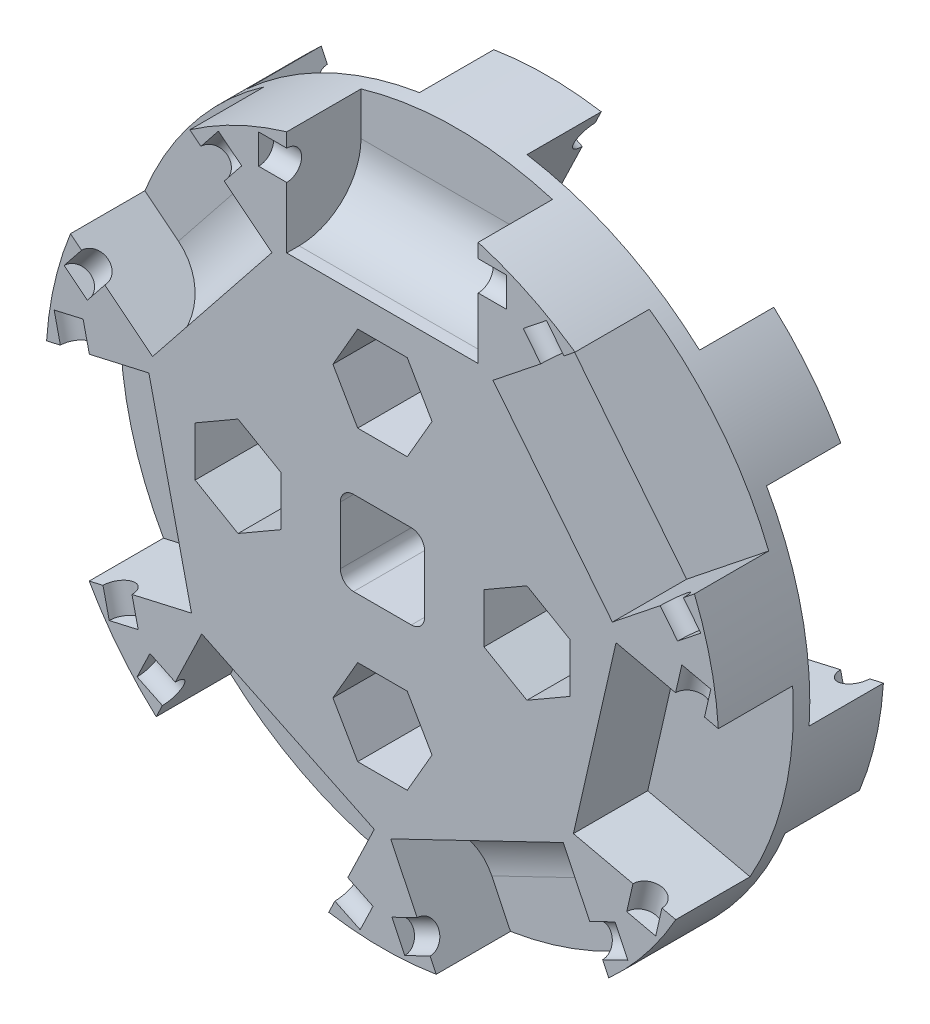
SolidWorks part; units mm, degrees
other "Markup1"
sketch "Sketch8" plane through (32.7336, 32.7336, 0) normal (0.5701, 0.1846, 0.8006) x (0.8043, 0.0736, -0.5897)
ref_plane "Front Plane" through (0, 0, 0) normal (0, 0, 1) x (1, 0, 0)
ref_plane "Top Plane" through (0, 0, 0) normal (0, 1, 0) x (1, 0, 0)
ref_plane "Right Plane" through (0, 0, 0) normal (1, 0, 0) x (0, 0, -1)
sketch "Sketch1" plane through (0, 0, 0) normal (0, 0, 1) x (1, 0, 0)
  circle A0 centre (0, 0) radius 25.8953
  dimension "D1" = 51.7906
extrude "Boss-Extrude2" add sketch "Sketch1" against normal blind 6.35
sketch "Sketch2" plane through (0, 0, 0) normal (0, 0, 1) x (1, 0, 0)
  line L1 (-12.7, 25.8953) -> (12.7, 25.8953) construction
  line L2 (-7.366, 27.1653) -> (7.366, 27.1653)
  line L3 (-7.366, 27.1653) -> (-7.366, 16.7513)
  line L4 (-7.366, 16.7513) -> (7.366, 16.7513)
  line L5 (7.366, 27.1653) -> (7.366, 16.7513)
  line L6 (-7.366, 27.1653) -> (7.366, 16.7513) construction
  line L7 (-7.366, 16.7513) -> (7.366, 27.1653) construction
  line L35 (0, 0) -> (0, 25.8953) construction
  circle A1 centre (0, 0) radius 25.8953 construction
  point P10 (0, 21.9583)
  circle M7 centre (0, 0) radius 25.8953
  dimension "D1" = 14.732
  dimension "D2" = 10.414
  dimension "D3" = 1.27
  dimension "D4" = 25.4
extrude "Cut-Extrude2" cut sketch "Sketch2" against normal blind 5.715 contours L5 L3 L4 M7
pattern_circular "CirPattern1" count 7 over 360 about axis through (0, 0, 0) along (0, 0, 1) of "Cut-Extrude2"
ref_plane "Plane1" through (0, 0, 0) normal (1, 0, 0) x (0, 0, -1)
sketch "Sketch4" plane through (0, 0, 0) normal (1, 0, 0) x (0, 0, -1)
  line L0 (5.715, 16.7513) -> (0, 16.7513) construction
  circle A0 centre (0, 22.5933) radius 1.143
  dimension "D1" = 2.286
  dimension "D2" = 5.842
extrude "Cut-Extrude4" cut sketch "Sketch4" against normal mid plane 19.05
pattern_circular "CirPattern2" count 7 over 360 about axis through (0, 0, 0) along (0, 0, 1) of "Cut-Extrude4"
sketch "Sketch5" plane through (0, 0, 0) normal (0, 0, 1) x (1, 0, 0)
  line L1 (-3.2385, -3.2385) -> (3.2385, -3.2385)
  line L2 (-3.2385, -3.2385) -> (-3.2385, 3.2385)
  line L3 (-3.2385, 3.2385) -> (3.2385, 3.2385)
  line L4 (3.2385, -3.2385) -> (3.2385, 3.2385)
  line L5 (-3.2385, -3.2385) -> (3.2385, 3.2385) construction
  line L6 (-3.2385, 3.2385) -> (3.2385, -3.2385) construction
  point P0 (0, 0)
  dimension "D1" = 6.477
extrude "Cut-Extrude5" cut sketch "Sketch5" against normal through all
sketch "Sketch6" plane through (0, 0, -6.35) normal (0, 0, -1) x (-1, 0, 0)
  line L0 (11.1125, -3.8128) -> (14.4145, -1.9064)
  line L1 (14.4145, -1.9064) -> (14.4145, 1.9064)
  line L2 (14.4145, 1.9064) -> (11.1125, 3.8128)
  line L3 (3.8128, 11.1125) -> (1.9064, 14.4145)
  line L4 (1.9064, 14.4145) -> (-1.9064, 14.4145)
  line L5 (-1.9064, 14.4145) -> (-3.8128, 11.1125)
  line L6 (-3.8128, 11.1125) -> (-1.9064, 7.8105)
  line L7 (-1.9064, 7.8105) -> (1.9064, 7.8105)
  line L8 (1.9064, 7.8105) -> (3.8128, 11.1125)
  line L9 (11.1125, 3.8128) -> (7.8105, 1.9064)
  line L10 (7.8105, 1.9064) -> (7.8105, -1.9064)
  line L11 (7.8105, -1.9064) -> (11.1125, -3.8128)
  line L12 (-3.8128, -11.1125) -> (-1.9064, -14.4145)
  line L13 (-1.9064, -14.4145) -> (1.9064, -14.4145)
  line L14 (1.9064, -14.4145) -> (3.8128, -11.1125)
  line L15 (3.8128, -11.1125) -> (1.9064, -7.8105)
  line L16 (1.9064, -7.8105) -> (-1.9064, -7.8105)
  line L17 (-1.9064, -7.8105) -> (-3.8128, -11.1125)
  line L18 (-11.1125, 3.8128) -> (-14.4145, 1.9064)
  line L19 (-14.4145, 1.9064) -> (-14.4145, -1.9064)
  line L20 (-14.4145, -1.9064) -> (-11.1125, -3.8128)
  line L21 (-11.1125, -3.8128) -> (-7.8105, -1.9064)
  line L22 (-7.8105, -1.9064) -> (-7.8105, 1.9064)
  line L23 (-7.8105, 1.9064) -> (-11.1125, 3.8128)
  circle A4 centre (0, 11.1125) radius 3.302 construction
  circle A5 centre (11.1125, 0) radius 3.302 construction
  circle A6 centre (0, -11.1125) radius 3.302 construction
  circle A7 centre (-11.1125, 0) radius 3.302 construction
  dimension "D3" = 4
  dimension "D1" = 6.604
  dimension "D2" = 11.1125
extrude "Cut-Extrude7" cut sketch "Sketch6" against normal through all
sketch "Sketch9" plane through (0, 0, -6.35) normal (0, 0, -1) x (-1, 0, 0)
  line L0 (3.2385, -3.2385) -> (-3.2385, -3.2385) construction
  line L1 (-3.2385, 3.2385) -> (3.2385, 3.2385)
  line L2 (-3.2385, 3.2385) -> (-3.2385, -3.2385)
  line L3 (-3.2385, -3.2385) -> (3.2385, -3.2385)
  line L4 (3.2385, 3.2385) -> (3.2385, -3.2385)
  line L5 (-3.2385, 3.2385) -> (3.2385, -3.2385) construction
  line L6 (-3.2385, -3.2385) -> (3.2385, 3.2385) construction
  line L7 (11.1125, -3.8128) -> (14.4145, -1.9064)
  line L8 (3.8128, 11.1125) -> (1.9064, 14.4145)
  line L9 (1.9064, 14.4145) -> (-1.9064, 14.4145)
  line L10 (-1.9064, 14.4145) -> (-3.8128, 11.1125)
  line L11 (-3.8128, 11.1125) -> (-1.9064, 7.8105)
  line L12 (-1.9064, 7.8105) -> (1.9064, 7.8105)
  line L13 (1.9064, 7.8105) -> (3.8128, 11.1125)
  line L14 (14.4145, -1.9064) -> (14.4145, 1.9064)
  line L15 (14.4145, 1.9064) -> (11.1125, 3.8128)
  line L16 (11.1125, 3.8128) -> (7.8105, 1.9064)
  line L17 (7.8105, 1.9064) -> (7.8105, -1.9064)
  line L18 (7.8105, -1.9064) -> (11.1125, -3.8128)
  line L19 (-3.8128, -11.1125) -> (-1.9064, -14.4145)
  line L20 (-1.9064, -14.4145) -> (1.9064, -14.4145)
  line L21 (1.9064, -14.4145) -> (3.8128, -11.1125)
  line L22 (3.8128, -11.1125) -> (1.9064, -7.8105)
  line L23 (1.9064, -7.8105) -> (-1.9064, -7.8105)
  line L24 (-1.9064, -7.8105) -> (-3.8128, -11.1125)
  line L25 (-11.1125, 3.8128) -> (-14.4145, 1.9064)
  line L26 (-14.4145, 1.9064) -> (-14.4145, -1.9064)
  line L27 (-14.4145, -1.9064) -> (-11.1125, -3.8128)
  line L28 (-11.1125, -3.8128) -> (-7.8105, -1.9064)
  line L29 (-7.8105, -1.9064) -> (-7.8105, 1.9064)
  line L30 (-7.8105, 1.9064) -> (-11.1125, 3.8128)
  line L31 (-1.9064, 7.8105) -> (1.9064, 7.8105) construction
  circle A0 centre (0, 0) radius 25.8953
  circle A5 centre (0, 11.1125) radius 3.302 construction
  circle A6 centre (11.1125, 0) radius 3.302 construction
  circle A7 centre (0, -11.1125) radius 3.302 construction
  circle A8 centre (-11.1125, 0) radius 3.302 construction
  circle A9 centre (0, 0) radius 25.8953 construction
  dimension "D3" = 4
extrude "Boss-Extrude3" add sketch "Sketch9" along normal blind 6.35
sketch "Sketch10" plane through (0, 0, -12.7) normal (0, 0, -1) x (-1, 0, 0)
  line L0 (-23.9355, 23.3309) -> (1.4645, 23.3309) construction
  line L1 (-0.6316, 18.2884) -> (-13.9047, 11.8964)
  line L2 (-0.6316, 18.2884) -> (-5.15, 27.6711)
  line L3 (-5.15, 27.6711) -> (-18.4231, 21.2791)
  line L4 (-13.9047, 11.8964) -> (-18.4231, 21.2791)
  line L5 (-0.6316, 18.2884) -> (-18.4231, 21.2791) construction
  line L6 (-5.15, 27.6711) -> (-13.9047, 11.8964) construction
  line L7 (0, 0) -> (-11.2355, 23.3309) construction
  line L8 (0, 0) -> (0, 40.3277) construction
  circle A2 centre (0, 0) radius 25.8953 construction
  point P8 (-9.5273, 19.7837)
  dimension "D1" = 1.27
  dimension "D2" = 14.732
  dimension "D3" = 10.414
  dimension "D4" = 25.4
  dimension "D5" = 25.714
extrude "Cut-Extrude8" cut sketch "Sketch10" against normal blind 5.715
pattern_circular "CirPattern3" count 7 over 360 about axis through (0, 0, 0) along (0, 0, 1) of "Cut-Extrude8"
ref_plane "Plane2" through (0, 0, 0) normal (-0.901, 0.4339, 0) x (0, 0, -1)
sketch "Sketch11" plane through (0, 0, 0) normal (-0.901, 0.4339, 0) x (0, 0, -1)
  line L5 (6.985, -16.7513) -> (12.7, -16.7513) construction
  line L6 (12.7, -24.8256) -> (12.7, -21.2375) construction
  circle A0 centre (12.7, -22.5933) radius 1.143
  dimension "D1" = 2.286
  dimension "D2" = 5.842
extrude "Cut-Extrude9" cut sketch "Sketch11" against normal mid plane 19.05
pattern_circular "CirPattern4" count 7 over 360 about axis through (0, 0, 0) along (0, 0, 1) of "Cut-Extrude9"
fillet "Fillet1" radius 4.7625 10 edges at (-13.0967, 10.4443, -5.715) (0, 16.7513, -5.715) (7.2681, 15.0924, -6.985) (13.0967, -10.4443, -6.985) (0, -16.7513, -6.985) (7.2681, -15.0924, -5.715) (-13.0967, -10.4443, -6.985) (16.3313, 3.7275, -6.985) (-16.3313, -3.7275, -5.715) (-7.2681, -15.0924, -5.715)
fillet "Fillet2" radius 1.016 4 edges at (3.2385, -3.2385, -6.35) (3.2385, 3.2385, -6.35) (-3.2385, 3.2385, -6.35) (-3.2385, -3.2385, -6.35)
